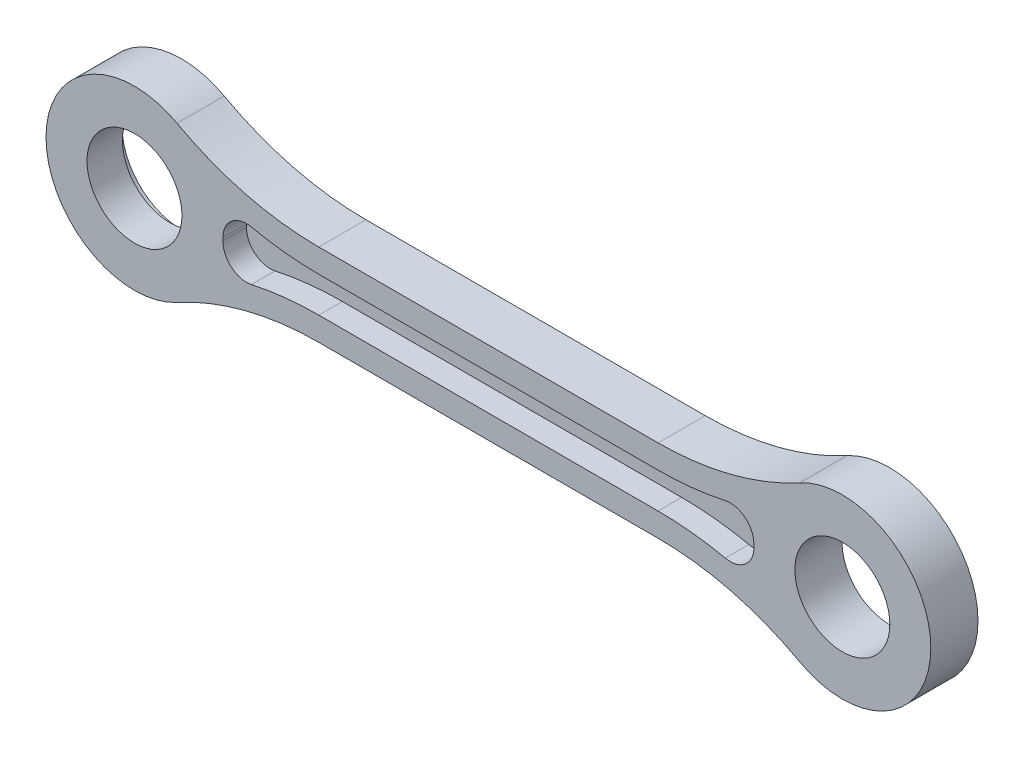
SolidWorks part; units mm, degrees
material "6061 合金"
ref_plane "前视基准面" through (0, 0, 0) normal (0, 0, 1) x (1, 0, 0)
ref_plane "上视基准面" through (0, 0, 0) normal (0, 1, 0) x (1, 0, 0)
ref_plane "右视基准面" through (0, 0, 0) normal (1, 0, 0) x (0, 0, -1)
other "Configuration Table"
sketch "草图1" plane through (0, 0, 0) normal (0, 0, 1) x (1, 0, 0)
  line L0 (-30, 0) -> (30, 0) construction
  line L1 (-30, 7.5) -> (30, 7.5)
  line L2 (-30, -7.5) -> (30, -7.5)
  arc A0 (-30, 7.5) -> (-30, -7.5) centre (-30, 0) ccw
  arc A1 (30, -7.5) -> (30, 7.5) centre (30, 0) ccw
  circle A2 centre (-30, 0) radius 4.025
  circle A3 centre (30, 0) radius 4.025
  point P2 (0, 0)
  dimension "D2" = 7.5
  dimension "D3" = 8.05
  dimension "D4" = 8.05
  dimension "D1" = 60
extrude "凸台-拉伸1" add sketch "草图1" along normal blind 4
sketch "草图2" plane through (0, 0, 4) normal (0, 0, 1) x (1, 0, 0)
  line L0 (-30, 0) -> (30, 0) construction
  line L2 (-14.3795, 3.5) -> (14.3795, 3.5)
  line L4 (-14.3795, -3.5) -> (14.3795, -3.5)
  line L6 (-23.3668, 3.5) -> (22.254, -3.3333) construction
  line L7 (-22.254, -3.3333) -> (23.3668, 3.5) construction
  line L9 (-30, -7.5) -> (30, -7.5)
  line L10 (30, 7.5) -> (-30, 7.5)
  line L11 (-30, -7.5) -> (30, -7.5)
  line L12 (30, 7.5) -> (-30, 7.5)
  arc A0 (-26.3953, 6.5769) -> (-26.3953, -6.5769) centre (-30, 0) ccw
  arc A1 (26.3953, -6.5769) -> (26.3953, 6.5769) centre (30, 0) ccw
  arc A2 (14.3795, 3.5) -> (26.3953, 6.5769) centre (14.3795, 28.5) ccw
  arc A3 (-14.3795, 3.5) -> (-26.3953, 6.5769) centre (-14.3795, 28.5) cw
  arc A4 (-30, 7.5) -> (-30, -7.5) centre (-30, 0) ccw
  arc A5 (30, -7.5) -> (30, 7.5) centre (30, 0) ccw
  arc A6 (-30, 7.5) -> (-30, -7.5) centre (-30, 0) ccw
  arc A7 (30, -7.5) -> (30, 7.5) centre (30, 0) ccw
  arc A8 (-14.3795, -3.5) -> (-26.3953, -6.5769) centre (-14.3795, -28.5) ccw
  arc A9 (14.3795, -3.5) -> (26.3953, -6.5769) centre (14.3795, -28.5) cw
  point P7 (0, 0)
  line M5 (-30, -7.5) -> (30, -7.5)
  line M7 (30, 7.5) -> (-30, 7.5)
  dimension "D3" = 25
  dimension "D4" = 7
  dimension "D2" = 0
extrude "切除-拉伸1" cut sketch "草图2" against normal blind 10 contours A3 L2 A2 A1 A0 M7 | A9 L4 A8 A0 A1 M5
sketch "草图4" plane through (0, 0, 0) normal (0, 0, -1) x (-1, 0, 0)
  circle A0 centre (30, 0) radius 5.05
  dimension "D1" = 10.1
extrude "切除-拉伸2" cut sketch "草图4" against normal blind 1 contours A0
sketch "草图5" plane through (0, 0, 4) normal (0, 0, 1) x (1, 0, 0)
  line L6 (-14.3795, -1.5) -> (14.3795, -1.5)
  line L7 (14.3795, 1.5) -> (-14.3795, 1.5)
  line L8 (-14.3795, -3.5) -> (14.3795, -3.5)
  line L9 (14.3795, 3.5) -> (-14.3795, 3.5)
  line L10 (-14.3795, -3.5) -> (14.3795, -3.5)
  line L11 (14.3795, 3.5) -> (-14.3795, 3.5)
  arc A6 (27.3565, -4.8231) -> (14.3795, -1.5) centre (14.3795, -28.5) ccw
  arc A7 (27.3565, -4.8231) -> (27.3565, 4.8231) centre (30, 0) ccw
  arc A8 (14.3795, 1.5) -> (27.3565, 4.8231) centre (14.3795, 28.5) ccw
  arc A9 (-27.3565, 4.8231) -> (-14.3795, 1.5) centre (-14.3795, 28.5) ccw
  arc A10 (-27.3565, 4.8231) -> (-27.3565, -4.8231) centre (-30, 0) ccw
  arc A11 (-14.3795, -1.5) -> (-27.3565, -4.8231) centre (-14.3795, -28.5) ccw
  arc A20 (-26.3953, 6.5769) -> (-14.3795, 3.5) centre (-14.3795, 28.5) ccw
  arc A21 (-26.3953, 6.5769) -> (-26.3953, -6.5769) centre (-30, 0) ccw
  arc A22 (-14.3795, -3.5) -> (-26.3953, -6.5769) centre (-14.3795, -28.5) ccw
  arc A23 (26.3953, -6.5769) -> (14.3795, -3.5) centre (14.3795, -28.5) ccw
  arc A24 (26.3953, -6.5769) -> (26.3953, 6.5769) centre (30, 0) ccw
  arc A25 (14.3795, 3.5) -> (26.3953, 6.5769) centre (14.3795, 28.5) ccw
  arc A26 (-26.3953, 6.5769) -> (-14.3795, 3.5) centre (-14.3795, 28.5) ccw
  arc A27 (-26.3953, 6.5769) -> (-26.3953, -6.5769) centre (-30, 0) ccw
  arc A28 (-14.3795, -3.5) -> (-26.3953, -6.5769) centre (-14.3795, -28.5) ccw
  arc A30 (26.3953, -6.5769) -> (14.3795, -3.5) centre (14.3795, -28.5) ccw
  arc A31 (26.3953, -6.5769) -> (26.3953, 6.5769) centre (30, 0) ccw
  arc A32 (14.3795, 3.5) -> (26.3953, 6.5769) centre (14.3795, 28.5) ccw
  circle A36 centre (-30, 0) radius 7.5
  circle A37 centre (30, 0) radius 7.5
  dimension "D1" = 0
  dimension "D2" = 2
extrude "切除-拉伸3" cut sketch "草图5" against normal blind 2
fillet "圆角2" radius 2 4 edges at (-23.1038, -2.9484, 3) (-23.1038, 2.9484, 3) (23.1038, -2.9484, 3) (23.1038, 2.9484, 3)
